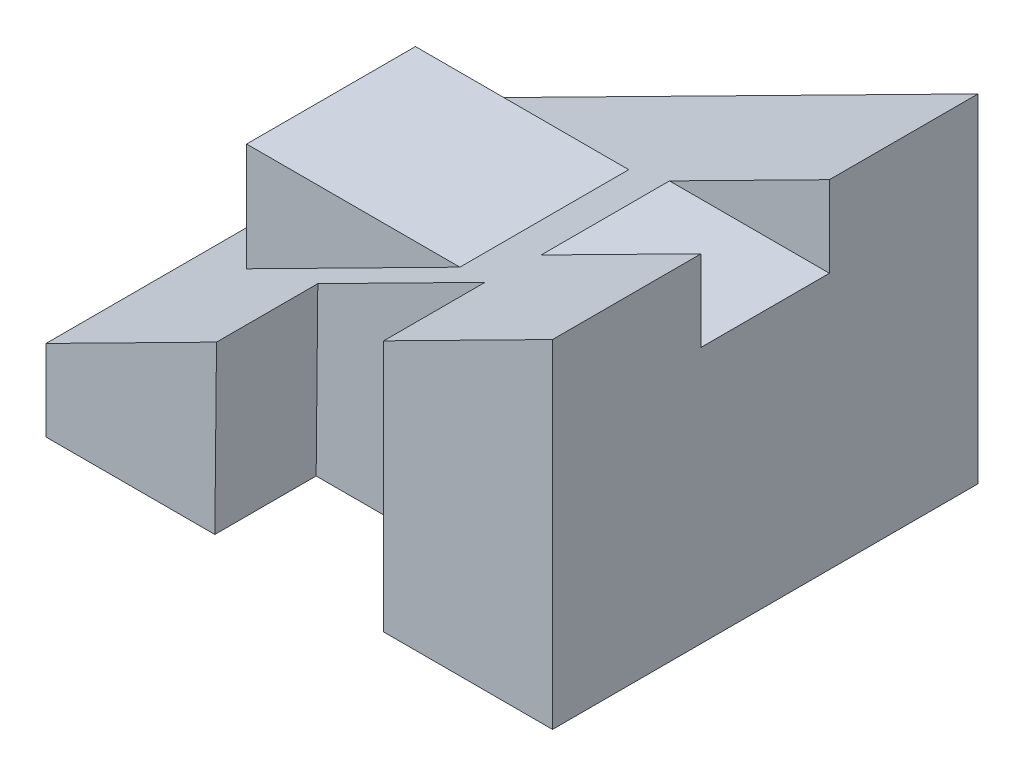
SolidWorks part; units mm, degrees
ref_plane "Front Plane" through (0, 0, 0) normal (0, 0, 1) x (1, 0, 0)
ref_plane "Top Plane" through (0, 0, 0) normal (0, 1, 0) x (1, 0, 0)
ref_plane "Right Plane" through (0, 0, 0) normal (1, 0, 0) x (0, 0, -1)
sketch "Sketch2" plane through (0, 0, 0) normal (0, 1, 0) x (1, 0, 0)
  line L1 (-37.5, -31.5) -> (37.5, -31.5)
  line L2 (-37.5, -31.5) -> (-37.5, 31.5)
  line L3 (-37.5, 31.5) -> (37.5, 31.5)
  line L4 (37.5, -31.5) -> (37.5, 31.5)
  line L5 (-37.5, -31.5) -> (37.5, 31.5) construction
  line L6 (-37.5, 31.5) -> (37.5, -31.5) construction
  point P0 (0, 0)
  dimension "D1" = 75
  dimension "D2" = 63
extrude "Boss-Extrude1" add sketch "Sketch2" along normal blind 50 contours L1 L4 L3 L2
sketch "Sketch4" plane through (0, 0, 31.5) normal (0, 0, 1) x (1, 0, 0)
  line L1 (-37.5, 50) -> (-37.5, 0) construction
  line L2 (-37.5, 12) -> (37.5, 50)
  line L3 (37.5, 50) -> (-37.5, 50)
  line L4 (-37.5, 50) -> (-37.5, 12)
extrude "Cut-Extrude1" cut sketch "Sketch4" against normal blind 80
sketch "Sketch5" plane through (-12.4982, 24.6676, 0) normal (-0.452, 0.892, 0) x (0.892, 0.452, 0)
  line L0 (56.0496, -31.5) -> (56.0496, -9.5)
  line L1 (56.0496, -31.5) -> (56.0496, 31.5) construction
  dimension "D1" = 22
sketch "Sketch6" plane through (37.5, 0, 0) normal (1, 0, 0) x (0, 0, -1)
  line L0 (-9.5, 50) -> (-9.5, 38)
  line L1 (31.5, 50) -> (9.5, 50)
  line L2 (-31.5, 50) -> (31.5, 50) construction
  line L3 (9.5, 50) -> (9.5, 38)
  line L4 (9.5, 38) -> (-9.5, 38)
  line L5 (-9.5, 50) -> (9.5, 50)
  line M6 (31.5, 50) -> (-31.5, 50)
  dimension "D1" = 12
  dimension "D2" = 22
  dimension "D3" = 12
extrude "Cut-Extrude2" cut sketch "Sketch6" against normal blind 80 contours L4 L3 L0 M6
sketch "Sketch8" plane through (0, 0, 31.5) normal (0, 0, 1) x (1, 0, 0)
  line L0 (-12.5, 0) -> (12.5, 0)
  line L1 (-37.5, 0) -> (37.5, 0) construction
  line L2 (37.5, 0) -> (12.5, 0)
  line L3 (12.5, 0) -> (12.5, 39.2145)
  line L4 (-12.5, 0) -> (-12.1095, 39.2145)
  line L5 (12.5, 39.2145) -> (-12.1095, 39.2145)
  line M7 (37.5, 50) -> (-37.5, 12)
  line M9 (-37.5, 0) -> (37.5, 0)
  dimension "D2" = 25
extrude "Cut-Extrude3" cut sketch "Sketch8" against normal blind 15 contours L4 L3 M9 M7
ref_plane "Plane2" through (0, 0, 0) normal (0, 0, 1) x (1, 0, 0)
sketch "Sketch10" plane through (0, 0, 0) normal (0, 0, 1) x (1, 0, 0)
  line L0 (37.5, 50) -> (-37.5, 12) construction
  line L1 (4.7834, 33.4236) -> (-26.7956, 17.4236)
  line L3 (-26.7956, 17.4236) -> (-26.7956, 33.4236)
  line L4 (-26.7956, 33.4236) -> (4.7834, 33.4236)
  dimension "D1" = 12
  dimension "D2" = 16
extrude "Boss-Extrude2" add sketch "Sketch10" along normal mid plane 25
